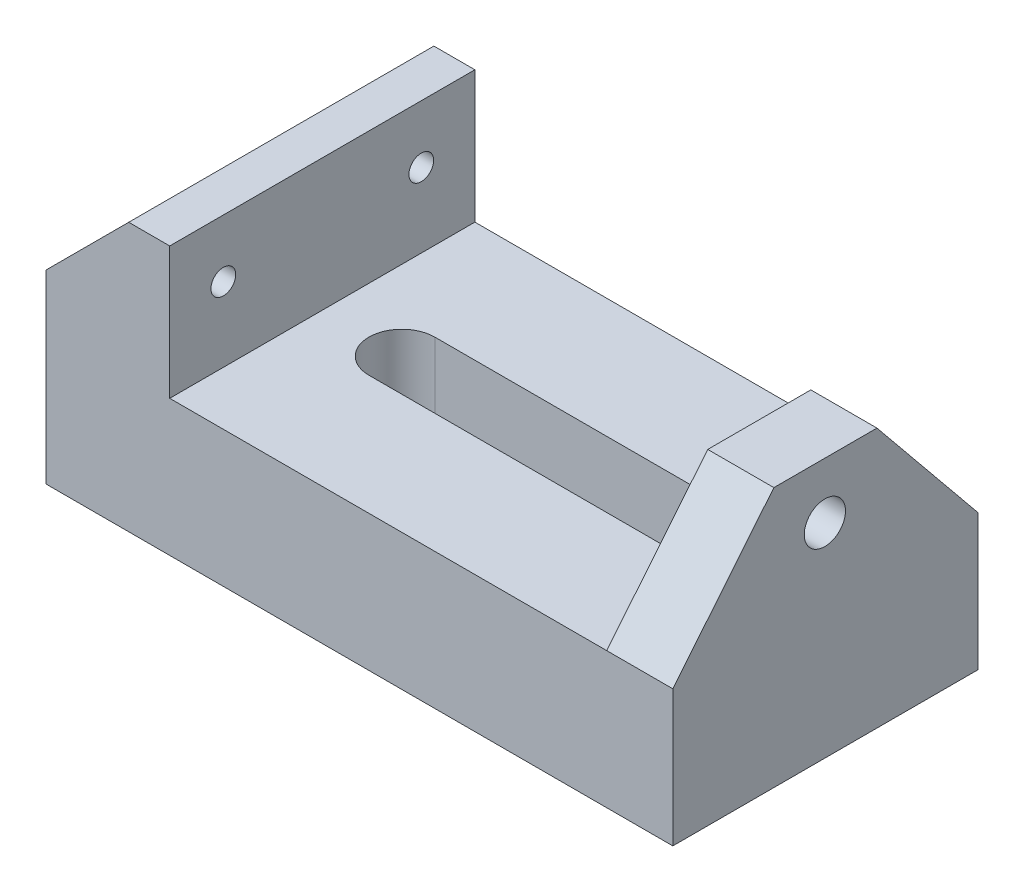
SolidWorks part; units mm, degrees
ref_plane "Front Plane" through (0, 0, 0) normal (0, 0, 1) x (1, 0, 0)
ref_plane "Top Plane" through (0, 0, 0) normal (0, 1, 0) x (1, 0, 0)
ref_plane "Right Plane" through (0, 0, 0) normal (1, 0, 0) x (0, 0, -1)
sketch "Sketch2" plane through (0, 0, 0) normal (0, 0, 1) x (1, 0, 0)
  line L0 (0, 0) -> (0, 30)
  line L1 (0, 30) -> (16.0367, 30)
  line L2 (16.0367, 30) -> (16.0367, -33)
  line L3 (16.0367, -33) -> (-135.9633, -33)
  line L4 (-135.9633, -33) -> (-135.9633, 18)
  line L6 (-115.9633, 32) -> (-105.9633, 32)
  line L7 (-105.9633, 32) -> (-105.9633, 0)
  line L8 (-105.9633, 0) -> (0, 0)
  line L9 (-135.9633, 18) -> (-135.9633, 32)
  line L10 (-135.9633, 32) -> (-115.9633, 32)
  line L11 (-135.9633, 18) -> (-142.5075, 18) construction
  dimension "D1" = 152
  dimension "D2" = 63
  dimension "D3" = 30
  dimension "D4" = 65
  dimension "D5" = 10
  dimension "D6" = 51
extrude "Boss-Extrude3" add sketch "Sketch2" along normal blind 74
sketch "Sketch11" plane through (0, 0, 74) normal (0, 0, 1) x (1, 0, 0)
  line L0 (-135.9633, 11.9437) -> (-135.9633, 32)
  line L1 (-135.9633, 32) -> (-135.9633, -33) construction
  line L2 (-135.9633, 32) -> (-115.907, 32)
  line L3 (-105.9633, 32) -> (-135.9633, 32) construction
  line L4 (-115.907, 32) -> (-135.9633, 11.9437)
  point P0 (-115.907, 32.5772)
  point P1 (-136.6523, 18.0367)
  dimension "D1" = 45
extrude "Cut-Extrude5" cut sketch "Sketch11" against normal blind 74
sketch "Sketch14" plane through (-105.9633, 0, 0) normal (1, 0, 0) x (0, 0, -1)
  line L0 (-74, 32) -> (0, 32) construction
  line L1 (-74, 0) -> (-74, 32) construction
  line L2 (0, 0) -> (0, 32) construction
  circle A0 centre (-61, 18) radius 3
  circle A1 centre (-13, 18) radius 3
  dimension "D1" = 14
  dimension "D2" = 13
  dimension "D3" = 6
  dimension "D4" = 14
  dimension "D5" = 13
  dimension "D6" = 6
extrude "Cut-Extrude6" cut sketch "Sketch14" against normal blind 74
sketch "Sketch15" plane through (-135.9633, 0, 0) normal (-1, 0, 0) x (0, 0, 1)
  line L0 (74, -33) -> (0, -33) construction
  line L2 (0, 11.9437) -> (74, 11.9437) construction
  circle A0 centre (36.6107, -4.8643) radius 8
  dimension "D1" = 16
  dimension "D2" = 28.1357
  dimension "D3" = 16.8079
extrude "Cut-Extrude7" cut sketch "Sketch15" against normal blind 13
sketch "Sketch16" plane through (0, 0, 0) normal (0, 1, 0) x (1, 0, 0)
  line L0 (-86.6731, -37) -> (-8.6731, -37) construction
  line L1 (-86.6731, -29) -> (-8.6731, -29)
  line L2 (-86.6731, -45) -> (-8.6731, -45)
  line L3 (0, 0) -> (-105.9633, 0) construction
  arc A0 (-86.6731, -29) -> (-86.6731, -45) centre (-86.6731, -37) ccw
  arc A1 (-8.6731, -45) -> (-8.6731, -29) centre (-8.6731, -37) ccw
  point P2 (-47.6731, -37)
  dimension "D1" = 78
  dimension "D2" = 16
  dimension "D3" = 37
extrude "Cut-Extrude8" cut sketch "Sketch16" against normal blind 90
sketch "Sketch18" plane through (0, 0, 74) normal (0, 0, 1) x (1, 0, 0)
  line L0 (0, 0) -> (54.5962, 0) construction
sketch "Sketch19" plane through (16.0367, 0, 0) normal (1, 0, 0) x (0, 0, -1)
  line L0 (-74, 30) -> (-74, 0)
  line L1 (-74, 0) -> (-74, 32) construction
  line L2 (-74, -33) -> (-74, 30) construction
  line L3 (-74, 0) -> (-49.5, 30)
  line L4 (-74, 30) -> (0, 30) construction
  line L5 (-49.5, 30) -> (-74, 30)
  line L6 (0, 0) -> (0, 30)
  line L7 (0, 30) -> (-24.5, 30)
  line L8 (-24.5, 30) -> (0, 0)
  dimension "D1" = 25
extrude "Cut-Extrude10" cut sketch "Sketch19" against normal blind 22
sketch "Sketch20" plane through (16.0367, 0, 0) normal (1, 0, 0) x (0, 0, -1)
  line L0 (-49.5, 30) -> (-24.5, 30) construction
  circle A0 centre (-37.1356, 16.44) radius 5
  dimension "D1" = 10
  dimension "D2" = 13.56
extrude "Cut-Extrude11" cut sketch "Sketch20" against normal blind 22
